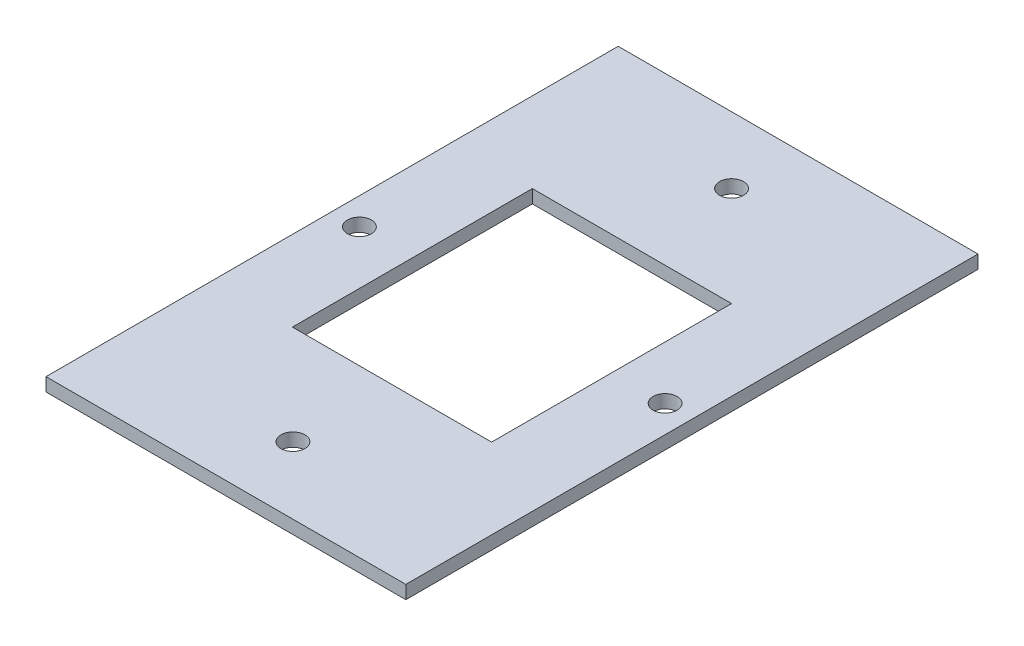
SolidWorks part; units mm, degrees
ref_plane "Front Plane" through (0, 0, 0) normal (0, 0, 1) x (1, 0, 0)
ref_plane "Top Plane" through (0, 0, 0) normal (0, 1, 0) x (1, 0, 0)
ref_plane "Right Plane" through (0, 0, 0) normal (1, 0, 0) x (0, 0, -1)
sketch "Sketch1" plane through (0, 0, 0) normal (0, 1, 0) x (1, 0, 0)
  line L1 (-27.07, -43.05) -> (27.07, -43.05)
  line L2 (-27.07, -43.05) -> (-27.07, 43.05)
  line L3 (-27.07, 43.05) -> (27.07, 43.05)
  line L4 (27.07, -43.05) -> (27.07, 43.05)
  line L5 (-27.07, -43.05) -> (27.07, 43.05) construction
  line L6 (-27.07, 43.05) -> (27.07, -43.05) construction
  point P0 (0, 0)
  dimension "D1" = 86.1
  dimension "D2" = 54.14
extrude "Boss-Extrude1" add sketch "Sketch1" along normal blind 2
sketch "Sketch3" plane through (0, 2, 0) normal (0, 1, 0) x (1, 0, 0)
  line L1 (-14.9873, -18.05) -> (14.9873, -18.05)
  line L2 (-14.9873, -18.05) -> (-14.9873, 18.05)
  line L3 (-14.9873, 18.05) -> (14.9873, 18.05)
  line L4 (14.9873, -18.05) -> (14.9873, 18.05)
  line L5 (-14.9873, -18.05) -> (14.9873, 18.05) construction
  line L6 (-14.9873, 18.05) -> (14.9873, -18.05) construction
  circle A0 centre (22.9873, 0.05) radius 1.8
  circle A1 centre (-0.0127, 33.05) radius 1.8
  circle A2 centre (-0.0127, -32.95) radius 1.8
  circle A3 centre (-23.0127, 0.05) radius 1.8
  point P12 (0, 0)
extrude "Cut-Extrude1" cut sketch "Sketch3" against normal blind 2
